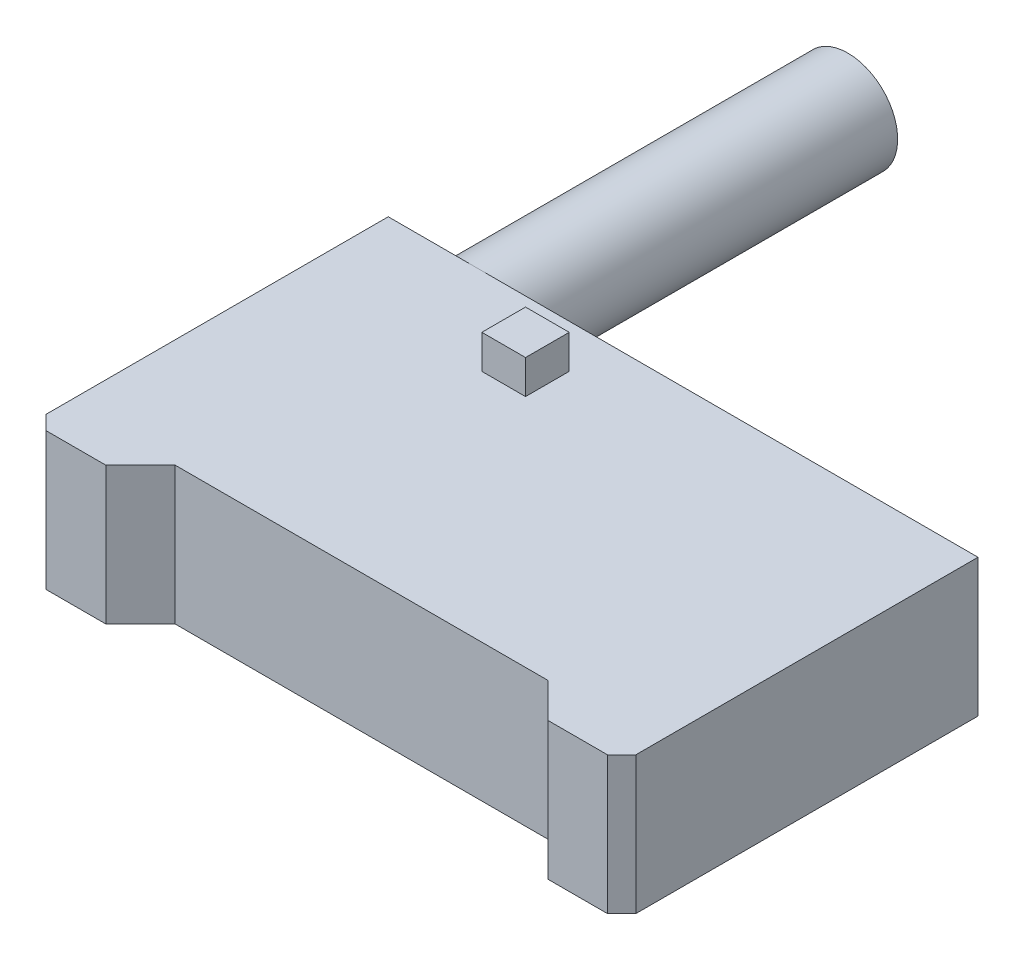
SolidWorks part; units mm, degrees
ref_plane "Front Plane" through (0, 0, 0) normal (0, 0, 1) x (1, 0, 0)
ref_plane "Top Plane" through (0, 0, 0) normal (0, 1, 0) x (1, 0, 0)
ref_plane "Right Plane" through (0, 0, 0) normal (1, 0, 0) x (0, 0, -1)
sketch "Sketch2" plane through (0, 0, 0) normal (0, 1, 0) x (1, 0, 0)
  line L0 (-19.9136, -17.6149) -> (-16.7894, -14.4907)
  line L1 (26.5684, -14.4907) -> (-26.5684, -14.4907)
  line L2 (26.5684, -14.4907) -> (26.5684, 14.4907)
  line L3 (26.5684, 14.4907) -> (-26.5684, 14.4907)
  line L4 (-26.5684, -14.4907) -> (-26.5684, 14.4907)
  line L5 (26.5684, -14.4907) -> (-26.5684, 14.4907) construction
  line L6 (26.5684, 14.4907) -> (-26.5684, -14.4907) construction
  line L7 (-25.2984, -14.4907) -> (-19.9136, -14.4907)
  line L8 (-25.2984, -14.4907) -> (-25.2984, -17.6149)
  line L9 (-25.2984, -17.6149) -> (-19.9136, -17.6149)
  line L10 (-19.9136, -14.4907) -> (-19.9136, -17.6149)
  line L11 (-16.7894, -14.4907) -> (-19.9136, -14.4907)
  line L12 (-19.9136, -17.6149) -> (-19.9136, -14.4907)
  line L13 (-25.2984, -17.6149) -> (-26.5684, -16.3449)
  line L14 (-26.5684, -16.3449) -> (-26.5684, -14.4907)
  line L15 (-25.2984, -14.4907) -> (-26.5684, -14.4907)
  line L16 (0, 0) -> (0, -5.6556) construction
  line L17 (-26.5684, 14.4907) -> (26.5684, -14.4907) construction
  line L18 (25.2984, -14.4907) -> (26.5684, -14.4907)
  line L19 (26.5684, -16.3449) -> (26.5684, -14.4907)
  line L20 (25.2984, -17.6149) -> (26.5684, -16.3449)
  line L21 (19.9136, -17.6149) -> (19.9136, -14.4907)
  line L22 (16.7894, -14.4907) -> (19.9136, -14.4907)
  line L23 (19.9136, -14.4907) -> (19.9136, -17.6149)
  line L24 (25.2984, -17.6149) -> (19.9136, -17.6149)
  line L25 (25.2984, -14.4907) -> (25.2984, -17.6149)
  line L26 (25.2984, -14.4907) -> (19.9136, -14.4907)
  line L27 (26.5684, -14.4907) -> (26.5684, 14.4907)
  line L28 (19.9136, -17.6149) -> (16.7894, -14.4907)
  point P0 (0, 0)
  dimension "D1" = 28.9814
  dimension "D2" = 53.1368
  dimension "D3" = 3.1242
  dimension "D4" = 5.3848
  dimension "D5" = 1.27
  dimension "D6" = 45
  dimension "D7" = 315
extrude "Boss-Extrude1" add sketch "Sketch2" along normal blind 12.3952 contours L4 L1 L2 L3 | L1 L25 L20 L19 | L25 L1 L21 L24 | L28 L21 L1 | L14 L13 L8 L1 | L10 L1 L8 L9 | L1 L10 L0
sketch "Sketch3" plane through (0, 0, -14.4907) normal (0, 0, -1) x (-1, 0, 0)
  line L0 (-26.5684, 12.3952) -> (26.5684, 12.3952) construction
  line L1 (26.5684, 12.3952) -> (26.5684, 0) construction
  circle A0 centre (18.6309, 7.9121) radius 4.4831
  point P2 (18.9806, 6.3113)
  point P5 (0, 0)
  dimension "D1" = 8.9662
  dimension "D2" = 7.9375
extrude "Boss-Extrude2" add sketch "Sketch3" along normal blind 33.4772 contours A0
sketch "Sketch5" plane through (0, 12.3952, 0) normal (0, 1, 0) x (1, 0, 0)
  line L0 (26.5684, 14.4907) -> (-18.6309, 14.4907) construction
  line L1 (-10.287, 10.5791) -> (-6.35, 10.5791)
  line L2 (-10.287, 10.5791) -> (-10.287, 6.6421)
  line L3 (-10.287, 6.6421) -> (-6.35, 6.6421)
  line L4 (-6.35, 10.5791) -> (-6.35, 6.6421)
  line L5 (-26.5684, -16.3449) -> (-26.5684, 14.4907) construction
  dimension "D1" = 3.9116
  dimension "D2" = 16.2814
  dimension "D3" = 3.937
  dimension "D4" = 3.937
extrude "Boss-Extrude3" add sketch "Sketch5" along normal blind 3.048
